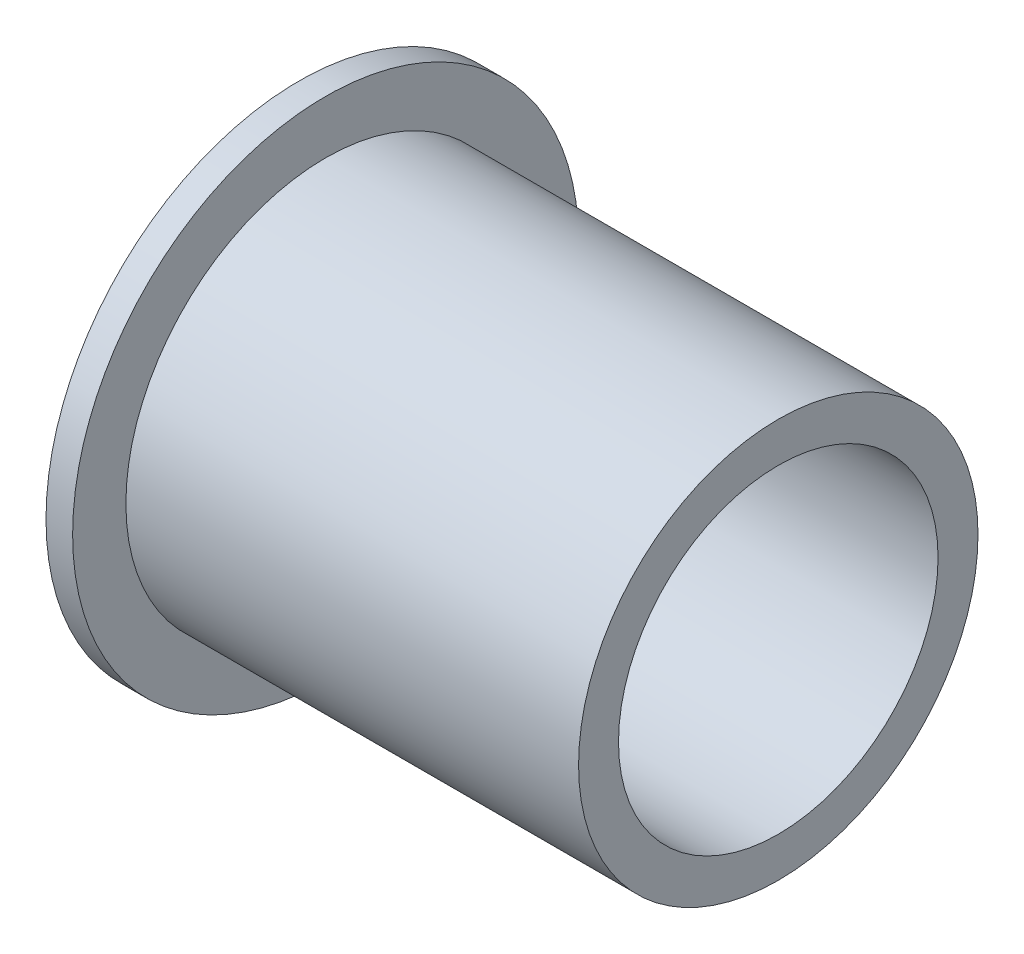
SolidWorks part; units mm, degrees
ref_plane "Front Plane" through (0, 0, 0) normal (0, 0, 1) x (1, 0, 0)
ref_plane "Top Plane" through (0, 0, 0) normal (0, 1, 0) x (1, 0, 0)
ref_plane "Right Plane" through (0, 0, 0) normal (1, 0, 0) x (0, 0, -1)
sketch "Sketch1" plane through (0, 0, 0) normal (0, 0, 1) x (1, 0, 0)
  line L0 (0, 0) -> (3.175, 0)
  line L1 (3.175, 0) -> (3.175, 6.35)
  line L2 (3.175, 6.35) -> (57.15, 6.35)
  line L3 (57.15, 6.35) -> (57.15, 11.1125)
  line L4 (57.15, 11.1125) -> (0, 11.1125)
  line L5 (0, 11.1125) -> (0, 0)
  line L6 (57.15, 30.1625) -> (0, 30.1625) construction
  line L7 (0, 49.2125) -> (0, 60.325) construction
  line L8 (57.15, 49.2125) -> (0, 49.2125) construction
  line L9 (57.15, 53.975) -> (57.15, 49.2125) construction
  line L10 (3.175, 53.975) -> (57.15, 53.975) construction
  line L11 (3.175, 60.325) -> (3.175, 53.975) construction
  line L12 (0, 60.325) -> (3.175, 60.325) construction
  dimension "E" = 3.175
  dimension "B" = 38.1
  dimension "C" = 57.15
  dimension "D" = 60.325
  dimension "A" = 47.625
revolve "Revolve1" add sketch "Sketch1" angle 360 about L6
